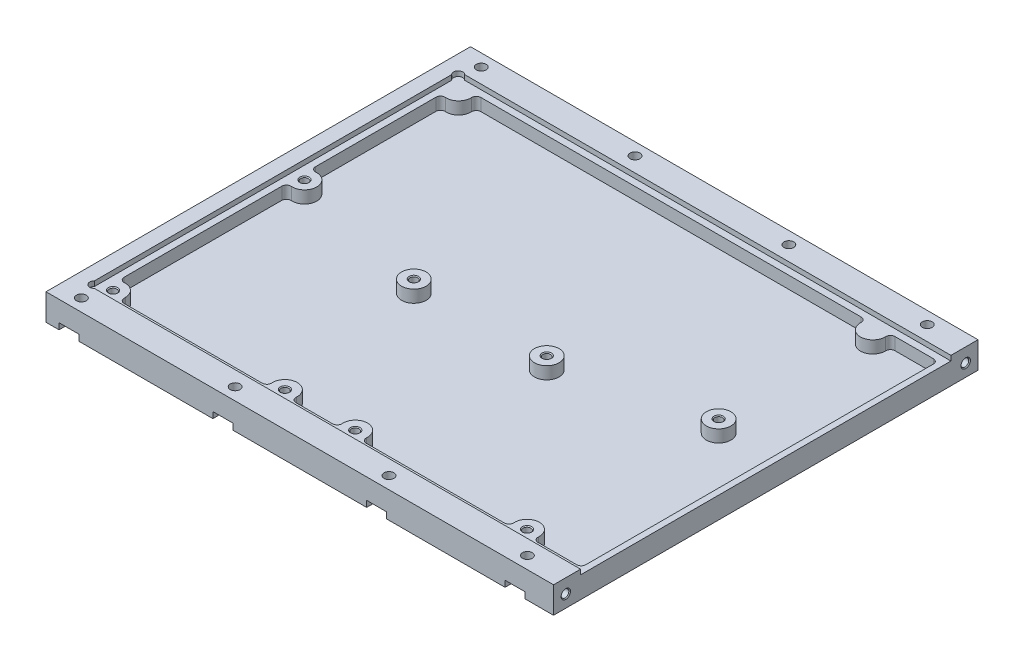
SolidWorks part; units mm, degrees
ref_plane "Front Plane" through (0, 0, 0) normal (0, 0, 1) x (1, 0, 0)
ref_plane "Top Plane" through (0, 0, 0) normal (0, 1, 0) x (1, 0, 0)
ref_plane "Right Plane" through (0, 0, 0) normal (1, 0, 0) x (0, 0, -1)
sketch "Sketch1" plane through (0, 0, 0) normal (0, 1, 0) x (1, 0, 0)
  line L1 (-85, 69) -> (80, 69)
  line L2 (-85, 69) -> (-85, -69)
  line L3 (-85, -69) -> (80, -69)
  line L4 (80, 69) -> (80, -69)
  dimension "D1" = 165
  dimension "D2" = 138
  dimension "D3" = 80
  dimension "D4" = 69
extrude "Boss-Extrude1" add sketch "Sketch1" along normal blind 7
sketch "Sketch4" plane through (0, 7, 0) normal (0, 1, 0) x (1, 0, 0)
  circle A0 centre (-76.1, -56.1) radius 1.25
  circle A1 centre (-20.22, -56.1) radius 1.25
  circle A2 centre (2.64, -56.1) radius 1.25
  circle A3 centre (58.49, -56.1) radius 1.25
  circle A4 centre (-76.1, 6.13) radius 1.25
  circle A5 centre (-30.38, -4.03) radius 1.25
  circle A6 centre (58.52, 6.16) radius 1.25
  circle A7 centre (12.8, -4) radius 1.25
  dimension "D1" = 2.5
  dimension "D2" = 2.5
  dimension "D3" = 2.5
  dimension "D4" = 2.5
  dimension "D5" = 2.5
  dimension "D6" = 2.5
  dimension "D7" = 2.5
  dimension "D8" = 2.5
  dimension "D9" = 22.86
  dimension "D10" = 55.88
  dimension "D11" = 55.85
  dimension "D12" = 45.72
  dimension "D13" = 10.16
  dimension "D14" = 62.23
  dimension "D15" = 62.26
  dimension "D16" = 10.16
  dimension "D17" = 45.72
  dimension "D18" = 43.18
  dimension "D19" = 12.8
  dimension "D20" = 4
extrude "Cut-Extrude2" cut sketch "Sketch4" against normal blind 5
cosmetic thread "Hole Thread9" parameters "D1"=4.45, "D2"=3
cosmetic thread "Hole Thread10" parameters "D1"=4.45, "D2"=3
cosmetic thread "Hole Thread11" parameters "D1"=4.45, "D2"=3
cosmetic thread "Hole Thread12" parameters "D1"=4.45, "D2"=3
cosmetic thread "Hole Thread13" parameters "D1"=4.45, "D2"=3
cosmetic thread "Hole Thread14" parameters "D1"=4.45, "D2"=3
cosmetic thread "Hole Thread15" parameters "D1"=4.45, "D2"=3
cosmetic thread "Hole Thread16" parameters "D1"=4.45, "D2"=3
cosmetic thread "Hole Thread17" parameters "D1"=4.45, "D2"=3
cosmetic thread "Hole Thread18" parameters "D1"=4.45, "D2"=3
cosmetic thread "Hole Thread19" parameters "D1"=4.45, "D2"=3
cosmetic thread "Hole Thread20" parameters "D1"=4.45, "D2"=3
cosmetic thread "Hole Thread21" parameters "D1"=4.45, "D2"=3
cosmetic thread "Hole Thread22" parameters "D1"=4.45, "D2"=3
cosmetic thread "Hole Thread23" parameters "D1"=4.45, "D2"=3
cosmetic thread "Hole Thread24" parameters "D1"=4.45, "D2"=3
cosmetic thread "Hole Thread25" parameters "D1"=4.45, "D2"=3
cosmetic thread "Hole Thread26" parameters "D1"=4.45, "D2"=3
cosmetic thread "Hole Thread27" parameters "D1"=4.45, "D2"=3
cosmetic thread "Hole Thread28" parameters "D1"=4.45, "D2"=3
cosmetic thread "Hole Thread29" parameters "D1"=4.45, "D2"=3
cosmetic thread "Hole Thread30" parameters "D1"=4.45, "D2"=3
cosmetic thread "Hole Thread31" parameters "D1"=4.45, "D2"=3
cosmetic thread "Hole Thread32" parameters "D1"=4.45, "D2"=3
sketch "Sketch5" plane through (0, 7, 0) normal (0, -1, 0) x (-1, 0, 0)
  line L0 (70.6, -58) -> (25.7054, -58)
  line L1 (-78, -56.5) -> (-78, 56.5)
  line L3 (78, -50.6) -> (78, 0.6446)
  line L7 (14.7346, -58) -> (2.8454, -58)
  line L8 (-8.1254, -58) -> (-53.0046, -58)
  line L9 (-63.9754, -58) -> (-76.5, -58)
  line L11 (72.1, -56.1) -> (72.1, -56.5)
  line L12 (76.1, -52.1) -> (76.5, -52.1)
  line L13 (70.6061, 58) -> (-53.0248, 58)
  line L15 (78, 11.6154) -> (78, 50.7546)
  line L16 (-64.0152, 58) -> (-76.5, 58)
  arc A0 (76.1, -52.1) -> (72.1, -56.1) centre (76.1, -56.1) ccw
  arc A1 (24.2094, -56.3909) -> (16.2306, -56.3909) centre (20.22, -56.1) ccw
  arc A2 (1.3494, -56.3909) -> (-6.6294, -56.3909) centre (-2.64, -56.1) ccw
  arc A3 (-54.5006, -56.3909) -> (-62.4794, -56.3909) centre (-58.49, -56.1) ccw
  circle A6 centre (30.38, -4.03) radius 4
  circle A7 centre (-12.8, -4) radius 4
  arc A8 (70.6, -58) -> (72.1, -56.5) centre (70.6, -56.5) ccw
  arc A9 (78, -50.6) -> (76.5, -52.1) centre (76.5, -50.6) cw
  arc A15 (-78, -56.5) -> (-76.5, -58) centre (-76.5, -56.5) ccw
  arc A16 (-63.9754, -58) -> (-62.4794, -56.3909) centre (-63.9754, -56.5) ccw
  arc A17 (-53.0046, -58) -> (-54.5006, -56.3909) centre (-53.0046, -56.5) cw
  arc A18 (-8.1254, -58) -> (-6.6294, -56.3909) centre (-8.1254, -56.5) ccw
  arc A19 (2.8454, -58) -> (1.3494, -56.3909) centre (2.8454, -56.5) cw
  arc A20 (14.7346, -58) -> (16.2306, -56.3909) centre (14.7346, -56.5) ccw
  arc A21 (24.2094, -56.3909) -> (25.7054, -58) centre (25.7054, -56.5) ccw
  arc A22 (76.3909, 10.1194) -> (76.3909, 2.1406) centre (76.1, 6.13) ccw
  circle A23 centre (-58.52, 6.16) radius 4
  arc A24 (78, 11.6154) -> (76.3909, 10.1194) centre (76.5, 11.6154) cw
  arc A25 (76.3909, 2.1406) -> (78, 0.6446) centre (76.5, 0.6446) cw
  arc A26 (-78, 56.5) -> (-76.5, 58) centre (-76.5, 56.5) cw
  arc A28 (72.1045, 56.4291) -> (76.3909, 52.2506) centre (76.1, 56.24) ccw
  arc A29 (72.1045, 56.4291) -> (70.6061, 58) centre (70.6061, 56.5) ccw
  arc A30 (76.3909, 52.2506) -> (78, 50.7546) centre (76.5, 50.7546) cw
  arc A31 (-62.5165, 56.4373) -> (-54.5235, 56.4373) centre (-58.52, 56.27) ccw
  arc A32 (-62.5165, 56.4373) -> (-64.0152, 58) centre (-64.0152, 56.5) ccw
  arc A33 (-54.5235, 56.4373) -> (-53.0248, 58) centre (-53.0248, 56.5) cw
  point P47 (78, 9.6499)
  point P59 (-62.0099, -58)
  point P64 (-6.1599, -58)
  point P69 (16.7001, -58)
  point P82 (-62.1265, 58)
  dimension "D1" = 8
  dimension "D2" = 8
  dimension "D3" = 58
  dimension "D4" = 8
  dimension "D5" = 8
  dimension "D6" = 8
  dimension "D7" = 8
  dimension "D8" = 8
  dimension "D13" = 1.5
  dimension "D14" = 1.5
  dimension "D15" = 1.5
  dimension "D12" = 8
  dimension "D16" = 1.5
  dimension "D17" = 1.5
  dimension "D18" = 8
  dimension "D20" = 1.5
  dimension "D21" = 8
  dimension "D23" = 1.5
  dimension "D9" = 58
  dimension "D10" = 78
  dimension "D11" = 78
  dimension "D19" = 50.11
  dimension "D22" = 50.11
extrude "Cut-Extrude3" cut sketch "Sketch5" along normal blind 4
sketch "Sketch6" plane through (0, 7, 0) normal (0, 1, 0) x (1, 0, 0)
  line L0 (-79.1393, 59.1393) -> (-80.2, 60.2) construction
  line L5 (-78.0787, 60.2) -> (80, 60.2)
  line L6 (-80.2, 58.0787) -> (-80.2, -58.0787)
  line L7 (-78.0787, -60.2) -> (80, -60.2)
  line L9 (80, -69) -> (80, 69) construction
  line L10 (-80.2, -60.2) -> (-79.1393, -59.1393) construction
  line L14 (80, 60.2) -> (80, 69)
  line L15 (80, 69) -> (-85, 69)
  line L16 (-85, 69) -> (-85, -69)
  line L17 (-85, -69) -> (80, -69)
  line L18 (80, -60.2) -> (80, -69)
  arc A0 (-78.0787, 60.2) -> (-80.2, 58.0787) centre (-79.1393, 59.1393) ccw
  arc A2 (-80.2, -58.0787) -> (-78.0787, -60.2) centre (-79.1393, -59.1393) ccw
  dimension "D5" = 3
  dimension "D13" = 3
  dimension "D2" = 120.4
  dimension "D3" = 80.2
  dimension "D4" = 60.2
  dimension "D6" = 45
  dimension "D7" = 1.0607
  dimension "D8" = 1.0607
  dimension "D14" = 45
  dimension "D15" = 1.0607
  dimension "D16" = 1.0607
extrude "Boss-Extrude2" add sketch "Sketch6" along normal blind 1.6
sketch "Sketch7" plane through (0, 8.6, 0) normal (0, 1, 0) x (1, 0, 0)
  line L5 (80, -60.2) -> (-78.0787, -60.2) construction
  line L6 (-85, -69) -> (80, -69) construction
  circle A0 centre (-77.5, -65) radius 1.6
  circle A1 centre (-27.5, -65) radius 1.6
  circle A2 centre (22.5, -65) radius 1.6
  circle A3 centre (67.5, -65) radius 1.6
  circle A4 centre (-77.5, 65) radius 1.6
  circle A5 centre (-27.5, 65) radius 1.6
  circle A6 centre (22.5, 65) radius 1.6
  circle A7 centre (67.5, 65) radius 1.6
  point P19 (0, 0)
  point P20 (0, 0)
  point P21 (0, 0)
  point P22 (0, 0)
  point P23 (0, 0)
  dimension "D5" = 3.2
  dimension "D6" = 3.2
  dimension "D7" = 3.2
  dimension "D8" = 3.2
  dimension "D11" = 3.2
  dimension "D12" = 3.2
  dimension "D13" = 3.2
  dimension "D14" = 3.2
  dimension "D1" = 50
  dimension "D2" = 45
  dimension "D3" = 50
  dimension "D4" = 27.5
  dimension "D9" = 65
  dimension "D10" = 65
  dimension "D15" = 4.8
  dimension "D16" = 4
extrude "Cut-Extrude4" cut sketch "Sketch7" against normal up to next
sketch "Sketch8" plane through (0, 0, 0) normal (0, -1, 0) x (-1, 0, 0)
  line L0 (-70.75, -65) -> (-70.75, -69)
  line L1 (85, -69) -> (-80, -69) construction
  line L2 (-64.25, -65) -> (-64.25, -69)
  line L3 (-64.25, -69) -> (-70.75, -69)
  line L4 (-25.75, -65) -> (-25.75, -69)
  line L5 (-19.25, -65) -> (-19.25, -69)
  line L6 (-19.25, -69) -> (-25.75, -69)
  line L7 (24.25, -65) -> (24.25, -69)
  line L8 (30.75, -65) -> (30.75, -69)
  line L9 (30.75, -69) -> (24.25, -69)
  line L10 (74.25, -65) -> (74.25, -69)
  line L11 (80.75, -65) -> (80.75, -69)
  line L12 (80.75, -69) -> (74.25, -69)
  line L13 (80.75, 65) -> (80.75, 69)
  line L16 (80.75, 69) -> (74.25, 69)
  line L17 (-80, 69) -> (85, 69) construction
  line L18 (74.25, 69) -> (74.25, 65)
  line L19 (30.75, 65) -> (30.75, 69)
  line L20 (30.75, 69) -> (24.25, 69)
  line L21 (24.25, 69) -> (24.25, 65)
  line L22 (-19.25, 65) -> (-19.25, 69)
  line L23 (-19.25, 69) -> (-25.75, 69)
  line L24 (-25.75, 69) -> (-25.75, 65)
  line L25 (-64.25, 65) -> (-64.25, 69)
  line L26 (-64.25, 69) -> (-70.75, 69)
  line L27 (-70.75, 69) -> (-70.75, 65)
  arc A0 (-19.25, -65) -> (-25.75, -65) centre (-22.5, -65) ccw
  arc A1 (30.75, -65) -> (24.25, -65) centre (27.5, -65) ccw
  arc A2 (-64.25, -65) -> (-70.75, -65) centre (-67.5, -65) ccw
  arc A3 (80.75, -65) -> (74.25, -65) centre (77.5, -65) ccw
  arc A4 (74.25, 65) -> (80.75, 65) centre (77.5, 65) ccw
  arc A5 (24.25, 65) -> (30.75, 65) centre (27.5, 65) ccw
  arc A6 (-25.75, 65) -> (-19.25, 65) centre (-22.5, 65) ccw
  arc A7 (-70.75, 65) -> (-64.25, 65) centre (-67.5, 65) ccw
  point P30 (-70.75, 67.5)
  point P33 (-19.75, 67.5)
  point P36 (30.25, 67.5)
  point P55 (81.25, 67.5)
  point P56 (-64.25, 69)
  point P57 (-66.15, 69)
  dimension "D1" = 6.5
  dimension "D2" = 6.5
  dimension "D3" = 6.5
  dimension "D4" = 6.5
  dimension "D5" = 6.5
  dimension "D6" = 6.5
  dimension "D7" = 6.5
  dimension "D8" = 6.5
extrude "Cut-Extrude5" cut sketch "Sketch8" against normal blind 2
hole_wizard "M3 Tapped Hole1" positions "Sketch9" profile "Sketch10" tap size "M3" standard "ISO"
sketch "Sketch9" plane through (0, 0, 0) normal (0, -1, 0) x (-1, 0, 0)
  point P0 (70, -64.6)
  point P2 (2.5, -64.6)
  point P4 (-60, -64.6)
  point P6 (2.5, 64.6)
  point P8 (70, 64.6)
  point P10 (-60, 64.6)
  point P13 (0, 0)
  point P14 (0, 0)
  point P15 (0, 0)
  point P16 (0, 0)
  point P17 (0, 0)
  point P19 (4.0709, -64.6)
  dimension "D1" = 64.6
  dimension "D2" = 64.6
  dimension "D3" = 70
  dimension "D4" = 60
  dimension "D5" = 2.5
sketch "Sketch10" plane through (-70, 0, 64.6) normal (1, 0, 0) x (0, 0, -1)
  line L0 (0, 0) -> (0, 8.2511)
  line L1 (0, 8.2511) -> (1.25, 7.5)
  line L2 (1.25, 7.5) -> (1.25, 0.275)
  line L3 (1.25, 0.275) -> (1.525, 0)
  line L5 (1.525, 0) -> (0, 0)
  line L6 (-1.25, 0.275) -> (-1.525, 0) construction
  line L10 (0, 8.2511) -> (-1.25, 7.5) construction
  line L11 (0, -6.35) -> (0, 107.95) construction
  dimension "Tap Drill Dia." = 2.5
  dimension "Tap Drill Depth" = 7.5
  dimension "Near C'Sink Dia." = 3.05
  dimension "Near C'Sink Angle" = 90
  dimension "Drill Angle" = 118
cosmetic thread "Hole Thread1" parameters "D1"=6, "D2"=3
cosmetic thread "Hole Thread2" parameters "D1"=6, "D2"=3
cosmetic thread "Hole Thread3" parameters "D1"=6, "D2"=3
cosmetic thread "Hole Thread4" parameters "D1"=6, "D2"=3
cosmetic thread "Hole Thread5" parameters "D1"=6, "D2"=3
cosmetic thread "Hole Thread6" parameters "D1"=6, "D2"=3
hole_wizard "M3 Tapped Hole2" positions "Sketch12" profile "Sketch11" tap size "M3" standard "ISO"
sketch "Sketch12" plane through (80, 0, 0) normal (1, 0, 0) x (0, 0, -1)
  line L0 (-69, 0) -> (69, 0) construction
  point P0 (-65, 4)
  point P1 (65, 4)
  point P4 (0, 0)
  dimension "D1" = 65
  dimension "D2" = 65
  dimension "D3" = 4
sketch "Sketch11" plane through (80, 4, 65) normal (0, 1, 0) x (0, 0, -1)
  line L0 (0, 0) -> (0, 8.2511)
  line L1 (0, 8.2511) -> (1.25, 7.5)
  line L2 (1.25, 7.5) -> (1.25, 0.275)
  line L3 (1.25, 0.275) -> (1.525, 0)
  line L5 (1.525, 0) -> (0, 0)
  line L6 (-1.25, 0.275) -> (-1.525, 0) construction
  line L10 (0, 8.2511) -> (-1.25, 7.5) construction
  line L11 (0, -6.35) -> (0, 107.95) construction
  dimension "Tap Drill Dia." = 2.5
  dimension "Tap Drill Depth" = 7.5
  dimension "Near C'Sink Dia." = 3.05
  dimension "Near C'Sink Angle" = 90
  dimension "Drill Angle" = 118
cosmetic thread "Hole Thread7" parameters "D1"=6, "D2"=3
cosmetic thread "Hole Thread8" parameters "D1"=6, "D2"=3
hole_wizard "M3 Tapped Hole3" positions "Sketch13" profile "Sketch14" tap size "M3" standard "ISO"
sketch "Sketch13" plane through (0, 7, 0) normal (0, 1, 0) x (1, 0, 0)
  point P0 (-76.1, 6.13)
  point P3 (-30.38, -4.03)
  point P6 (12.8, -4)
  point P9 (58.52, 6.16)
  point P12 (-76.1, -56.1)
  point P15 (-20.22, -56.1)
  point P18 (2.64, -56.1)
  point P21 (58.49, -56.1)
sketch "Sketch14" plane through (-76.1, 7, -6.13) normal (1, 0, 0) x (0, 0, 1)
  line L0 (0, 0) -> (0, 5.7511)
  line L1 (0, 5.7511) -> (1.25, 5)
  line L2 (1.25, 5) -> (1.25, 0.275)
  line L3 (1.25, 0.275) -> (1.525, 0)
  line L5 (1.525, 0) -> (0, 0)
  line L6 (-1.25, 0.275) -> (-1.525, 0) construction
  line L10 (0, 5.7511) -> (-1.25, 5) construction
  line L11 (0, -6.35) -> (0, 107.95) construction
  dimension "Tap Drill Dia." = 2.5
  dimension "Tap Drill Depth" = 5
  dimension "Near C'Sink Dia." = 3.05
  dimension "Near C'Sink Angle" = 90
  dimension "Drill Angle" = 118
